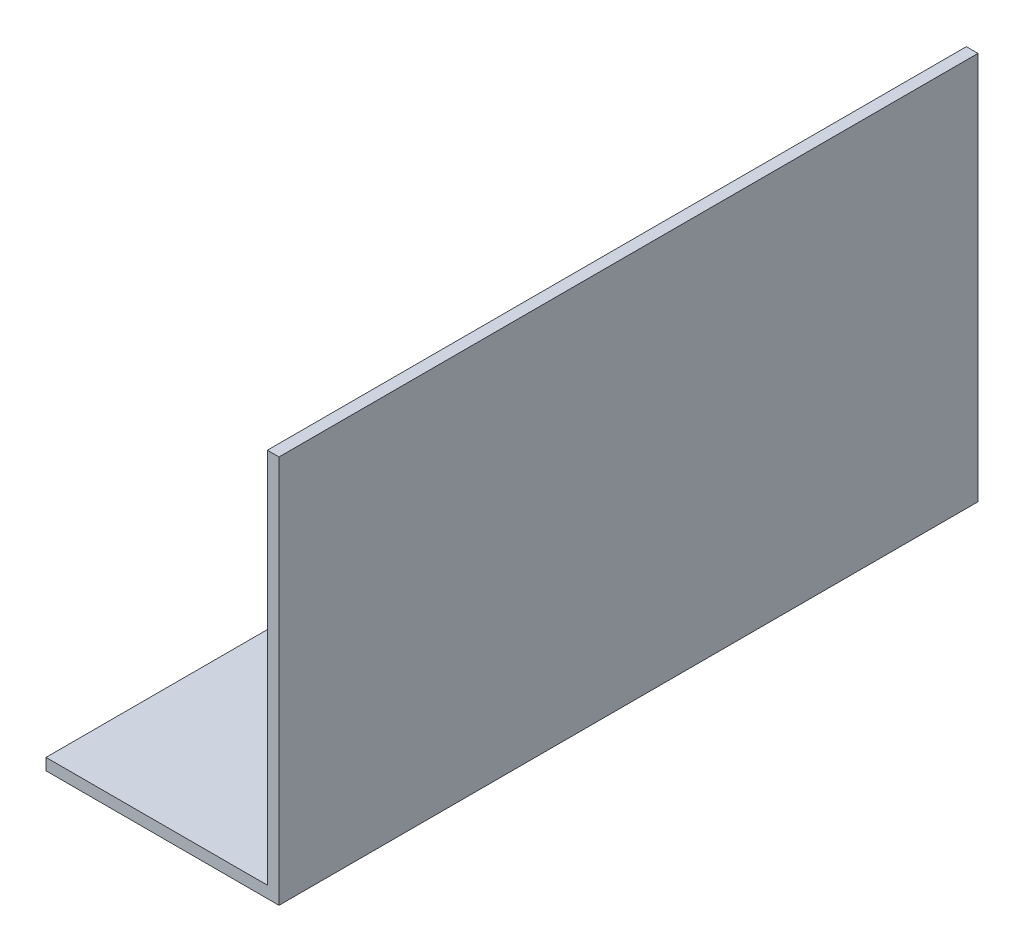
SolidWorks part; units mm, degrees
ref_plane "Front Plane" through (0, 0, 0) normal (0, 0, 1) x (1, 0, 0)
ref_plane "Top Plane" through (0, 0, 0) normal (0, 1, 0) x (1, 0, 0)
ref_plane "Right Plane" through (0, 0, 0) normal (1, 0, 0) x (0, 0, -1)
sketch "Sketch1" plane through (0, 0, 0) normal (0, 0, 1) x (1, 0, 0)
  line L0 (-12.1815, -30.3345) -> (44.8185, -30.3345)
  line L1 (44.8185, -30.3345) -> (44.8185, 66.6655)
  line L2 (-12.1815, -33.3345) -> (47.8185, -33.3345)
  line L3 (47.8185, -33.3345) -> (47.8185, 66.6655)
  line L4 (-12.1815, -30.3345) -> (-12.1815, -33.3345)
  line L5 (44.8185, 66.6655) -> (47.8185, 66.6655)
  dimension "D2" = 100
  dimension "D3" = 60
  dimension "D1" = 3
extrude "Boss-Extrude1" add sketch "Sketch1" along normal blind 180
